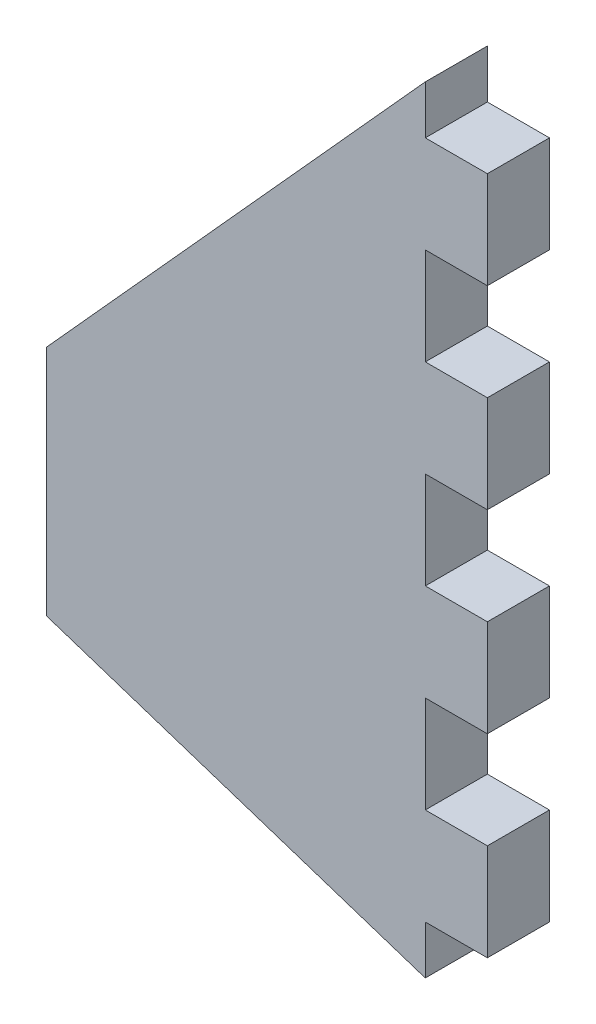
SolidWorks part; units mm, degrees
ref_plane "Piano frontale" through (0, 0, 0) normal (0, 0, 1) x (1, 0, 0)
ref_plane "Piano superiore" through (0, 0, 0) normal (0, 1, 0) x (1, 0, 0)
ref_plane "Piano destro" through (0, 0, 0) normal (1, 0, 0) x (0, 0, -1)
sketch "Schizzo1" plane through (0, 0, 0) normal (0, 0, 1) x (1, 0, 0)
  line L0 (-24.4, 23) -> (-24.4, 8)
  line L1 (-24.4, 8) -> (0, 0)
  line L2 (0, 0) -> (0, 50)
  line L3 (0, 50) -> (-24.4, 23)
  point P2 (0, 25)
  dimension "D1" = 50
  dimension "D2" = 15
  dimension "D3" = 24.4
  dimension "D4" = 8
extrude "Estrusione-Estrusione1" add sketch "Schizzo1" along normal blind 4
sketch "Schizzo2" plane through (0, 0, 4) normal (0, 0, 1) x (1, 0, 0)
  line L0 (0, 0) -> (0, 50) construction
  line L1 (0, 46.875) -> (4, 46.875)
  line L2 (0, 46.875) -> (0, 40.625)
  line L3 (0, 40.625) -> (4, 40.625)
  line L4 (4, 46.875) -> (4, 40.625)
  dimension "D1" = 6.25
  dimension "D2" = 4
  dimension "D3" = 3.125
extrude "Estrusione-Estrusione2" add sketch "Schizzo2" against normal blind 4
pattern_linear "Ripetizione a L1" count 4 spacing 12.5 along (0, -1, 0) of "Estrusione-Estrusione2"
equation "\"WFront\"= 140mm"
equation "\"HFront\"= 80mm"
equation "\"DFront\"= 4mm"
equation "\"WLeft\"= 50mm"
equation "\"HLeft\"= 80mm"
equation "\"DLeft\"= 4mm"
equation "\"WTop\"= 140mm"
equation "\"HTop\"= 50mm"
equation "\"DTop\"= 4mm"
equation "\"N_Denti_W\"= 10"
equation "\"N_Denti_H\"= 7"
equation "\"N_Denti_D\"= 4"
equation "\"HDistDenti\"= \"HFront\" / \"N_Denti_H\""
equation "\"WDistDenti\"= \"WFront\" / \"N_Denti_W\""
equation "\"DDistDenti\"= \"WLeft\" / \"N_Denti_D\""
equation "\"HDenti\"= \"HDistDenti\" / 2"
equation "\"WDenti\"= \"WDistDenti\" / 2"
equation "\"DDenti\"= \"DDistDenti\" / 2"
equation "\"WDisplay\"= 95mm"
equation "\"HDisplay\"= 61mm"
equation "\"CEnc\"= 7mm"
equation "\"Display_to_Enc_W\"= 11.5 + \"CEnc\" / 2"
equation "\"Display_to_Dx\"= 32mm"
equation "\"Display_to_Top\"= 10mm"
equation "\"Display_to_Enc_H\"= 24 + \"CEnc\" / 2"
equation "\"DMask\"= 3mm"
equation "\"D1@Estrusione-Estrusione1\"=\"DFront\""
equation "\"D1@Schizzo2\"=\"DDenti\""
equation "\"D2@Schizzo2\"=\"DFront\""
equation "\"D1@Estrusione-Estrusione2\"=\"DFront\""
equation "\"D1@Ripetizione a L1\"=\"N_Denti_D\""
equation "\"D3@Ripetizione a L1\"=\"DDistDenti\""
equation "\"D3@Schizzo2\"=\"DDenti\"/2"
